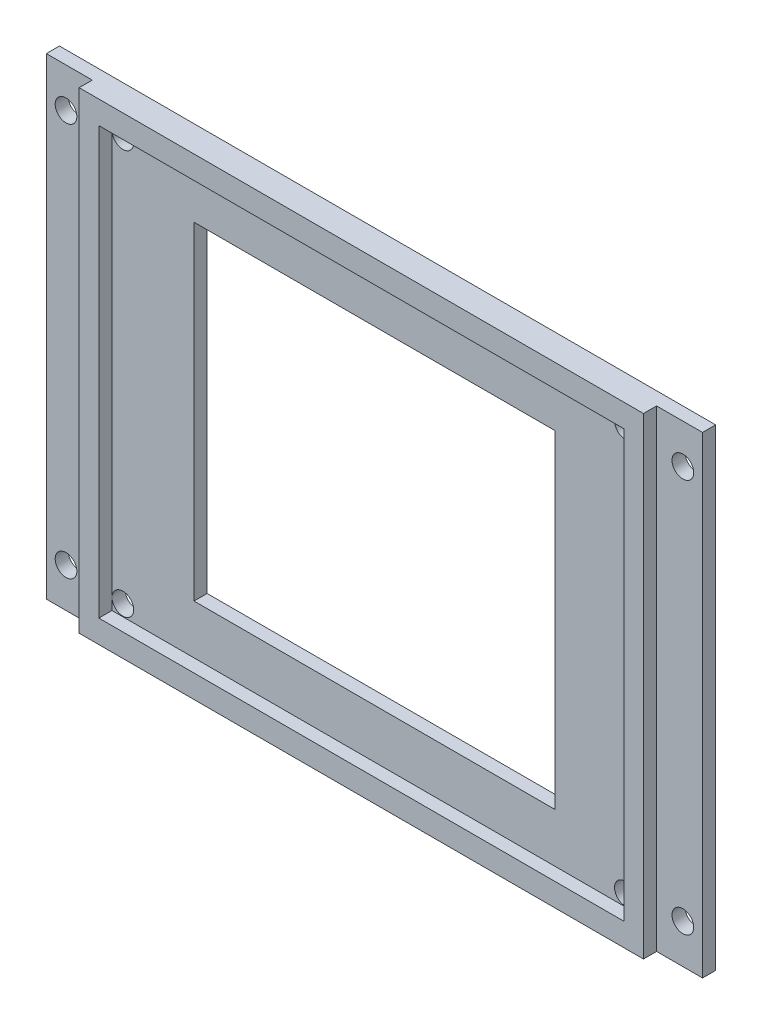
SolidWorks part; units mm, degrees
ref_plane "前视基准面" through (0, 0, 0) normal (0, 0, 1) x (1, 0, 0)
ref_plane "上视基准面" through (0, 0, 0) normal (0, 1, 0) x (1, 0, 0)
ref_plane "右视基准面" through (0, 0, 0) normal (1, 0, 0) x (0, 0, -1)
sketch "草图1" plane through (0, 0, 0) normal (0, 0, 1) x (1, 0, 0)
  line L1 (-50, 36) -> (50, 36)
  line L2 (-50, 36) -> (-50, -36)
  line L3 (-50, -36) -> (50, -36)
  line L4 (50, 36) -> (50, -36)
  line L5 (-50, 36) -> (50, -36) construction
  line L6 (-50, -36) -> (50, 36) construction
  point P0 (0, 0)
  dimension "D1" = 100
  dimension "D2" = 72
extrude "凸台-拉伸1" add sketch "草图1" along normal blind 4
sketch "草图2" plane through (0, 0, 4) normal (0, 0, 1) x (1, 0, 0)
  line L1 (-40, 32.5) -> (40, 32.5)
  line L2 (-40, 32.5) -> (-40, -32.5)
  line L3 (-40, -32.5) -> (40, -32.5)
  line L4 (40, 32.5) -> (40, -32.5)
  line L5 (-40, 32.5) -> (40, -32.5) construction
  line L6 (-40, -32.5) -> (40, 32.5) construction
  point P0 (0, 0)
  dimension "D1" = 80
  dimension "D2" = 65
extrude "切除-拉伸1" cut sketch "草图2" against normal blind 2
sketch "草图3" plane through (0, 0, 2) normal (0, 0, 1) x (1, 0, 0)
  circle A0 centre (-38.3404, 30.8364) radius 1.65
  circle A1 centre (38.2406, 30.8364) radius 1.65
  circle A2 centre (38.2406, -30.7586) radius 1.65
  circle A3 centre (-38.3404, -30.7586) radius 1.65
  point P8 (0, 0)
  point P9 (0, 0)
  point P10 (0, 0)
  point P11 (0, 0)
  point P12 (0, 0)
  point P13 (0, 0)
  point P14 (0, 0)
  point P15 (0, 0)
  point P16 (-37.8797, 25.6855)
  point P17 (-38.2948, 30.1481)
  point P18 (-38.2948, 30.667)
  point P19 (-38.3404, 30.8364)
  dimension "D1" = 3.3
  dimension "D2" = 3.3
  dimension "D3" = 3.3
  dimension "D4" = 3.3
  dimension "D5" = 76.581
  dimension "D6" = 76.581
  dimension "D7" = 61.595
extrude "切除-拉伸2" cut sketch "草图3" against normal blind 2
sketch "草图4" plane through (0, 0, 4) normal (0, 0, 1) x (1, 0, 0)
  circle A0 centre (-47, 30) radius 1.65
  circle A1 centre (47, 30) radius 1.65
  circle A2 centre (47, -30) radius 1.65
  circle A3 centre (-47, -30) radius 1.65
  point P8 (0, 0)
  point P9 (0, 0)
  point P10 (0, 0)
  point P11 (-47.8425, 29.8367)
  point P12 (-45.8707, 29.6292)
  point P13 (0, 0)
  point P14 (0, 0)
  dimension "D1" = 3.3
  dimension "D2" = 3.3
  dimension "D3" = 3.3
  dimension "D4" = 3.3
  dimension "D5" = 94
  dimension "D6" = 94
  dimension "D7" = 60
  dimension "D8" = 47
  dimension "D9" = 30
extrude "切除-拉伸3" cut sketch "草图4" against normal blind 4
sketch "草图5" plane through (0, 0, 4) normal (0, 0, 1) x (1, 0, 0)
  line L0 (-50, -36) -> (50, -36) construction
  line L1 (-50, 36) -> (-43, 36)
  line L2 (-50, 36) -> (-50, -36)
  line L3 (-50, -36) -> (-43, -36)
  line L4 (-43, 36) -> (-43, -36)
  line L6 (50, 36) -> (43, 36)
  line L7 (50, 36) -> (50, -36)
  line L8 (50, -36) -> (43, -36)
  line L9 (43, 36) -> (43, -36)
  dimension "D1" = 7
  dimension "D2" = 7
extrude "切除-拉伸4" cut sketch "草图5" against normal blind 2
sketch "草图6" plane through (0, 0, 2) normal (0, 0, 1) x (1, 0, 0)
  line L1 (-27.5, 25) -> (27.5, 25)
  line L2 (-27.5, 25) -> (-27.5, -25)
  line L3 (-27.5, -25) -> (27.5, -25)
  line L4 (27.5, 25) -> (27.5, -25)
  line L5 (-27.5, 25) -> (27.5, -25) construction
  line L6 (-27.5, -25) -> (27.5, 25) construction
  point P0 (0, 0)
  dimension "D1" = 55
  dimension "D2" = 50
extrude "切除-拉伸5" cut sketch "草图6" against normal blind 2
